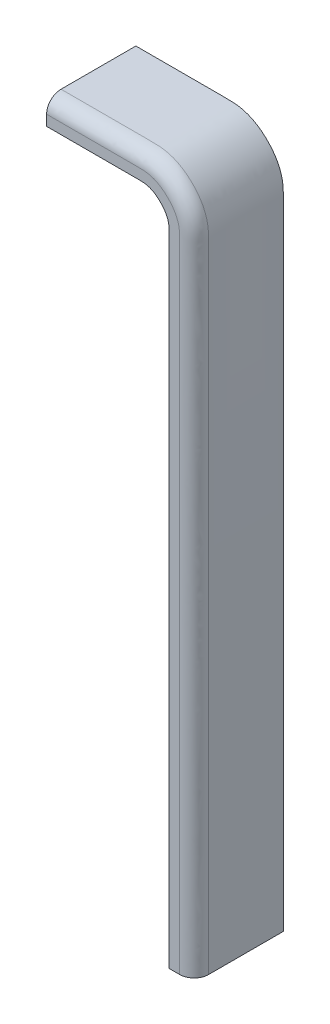
SolidWorks part; units mm, degrees
ref_plane "Front Plane" through (0, 0, 0) normal (0, 0, 1) x (1, 0, 0)
ref_plane "Top Plane" through (0, 0, 0) normal (0, 1, 0) x (1, 0, 0)
ref_plane "Right Plane" through (0, 0, 0) normal (1, 0, 0) x (0, 0, -1)
ref_plane "Plane1" through (47.5918, 0, 0) normal (1, 0, 0) x (0, 0, -1)
sketch "Sketch1" plane through (47.5918, 0, 0) normal (1, 0, 0) x (0, 0, -1)
  line L0 (32.6736, 0) -> (32.6736, 18.288)
  line L1 (-22.1044, 18.288) -> (32.6736, 18.288) construction
  line L2 (32.6736, 18.288) -> (-22.1044, 18.288)
  line L3 (32.6736, 0) -> (-32.6736, 0)
  line L4 (-32.6736, 0) -> (-32.6736, 7.7188)
  line L5 (-22.1044, 18.288) -> (-22.1044, 7.7188) construction
  line L6 (-22.1044, 7.7188) -> (-32.6736, 7.7188) construction
  arc A0 (-22.1044, 18.288) -> (-32.6736, 7.7188) centre (-22.1044, 7.7188) ccw
  arc A1 (-22.1044, 18.288) -> (-32.6736, 7.7188) centre (-22.1044, 7.7188) ccw construction
ref_plane "Plane2" through (0, 0, 0) normal (0, 1, 0) x (0, 0, 1)
sketch "Sketch2" plane through (0, 0, 0) normal (0, 1, 0) x (0, 0, 1)
  line L0 (-32.6736, 47.5918) -> (-32.6736, 137.3248) construction
  line L1 (-32.6736, 137.3248) -> (32.6736, 137.3248) construction
  line L2 (32.6736, 137.3248) -> (32.6736, 47.5918) construction
  line L3 (-32.6736, 47.5918) -> (32.6736, 47.5918) construction
ref_plane "Plane3" through (137.3248, 0, 0) normal (1, 0, 0) x (0, 0, 1)
sketch "Sketch3" plane through (137.3248, 0, 0) normal (1, 0, 0) x (0, 0, 1)
  line L0 (32.6736, 0) -> (32.6736, 489.0168) construction
  line L1 (32.6736, 489.0168) -> (-32.6736, 489.0168) construction
  line L2 (-32.6736, 489.0168) -> (-32.6736, 0) construction
  dimension "D1" = 489.0168
ref_plane "Plane4" through (0, 0, 32.6736) normal (0, 0, 1) x (1, 0, 0)
sketch "Sketch4" plane through (0, 0, 32.6736) normal (0, 0, 1) x (1, 0, 0)
  line L0 (47.5918, 0) -> (114.0521, 0) construction
  line L1 (137.3248, -489.0168) -> (137.3248, -23.2727) construction
  line L2 (137.3248, -23.2727) -> (114.0521, -23.2727) construction
  line L3 (114.0521, -23.2727) -> (114.0521, 0) construction
  arc A0 (114.0521, 0) -> (137.3248, -23.2727) centre (114.0521, -23.2727) cw
  spline S0 degree 3 poles (47.5918, 0) (69.7452, 0) (91.8986, 0) (114.0521, 0) (117.709, 0) (125.0229, 0) (137.3248, -12.3018) (137.3248, -19.6157) (137.3248, -23.2727) (137.3248, -178.5207) (137.3248, -333.7688) (137.3248, -489.0168) knots 0 0 0 0 0.117604 0.117604 0.117604 0.137018 0.156431 0.175845 0.175845 0.175845 1 1 1 1
sketch "Sketch5" plane through (47.5918, 0, 0) normal (1, 0, 0) x (0, 0, -1)
  line L15 (-32.6736, 0) -> (32.6736, 0)
  line L16 (-32.6736, 7.7188) -> (-32.6736, 0)
  line L17 (32.6736, 18.288) -> (-22.1044, 18.288)
  line L18 (32.6736, 0) -> (32.6736, 18.288)
  line L19 (-32.6736, 0) -> (32.6736, 0)
  line L20 (-32.6736, 7.7188) -> (-32.6736, 0)
  line L21 (32.6736, 18.288) -> (-22.1044, 18.288)
  line L22 (32.6736, 0) -> (32.6736, 18.288)
  arc A4 (-22.1044, 18.288) -> (-32.6736, 7.7188) centre (-22.1044, 7.7188) ccw
  arc A5 (-22.1044, 18.288) -> (-32.6736, 7.7188) centre (-22.1044, 7.7188) ccw
  dimension "D1" = 0
sweep "Sweep1" add profiles "Sketch5" path "Sketch4"
